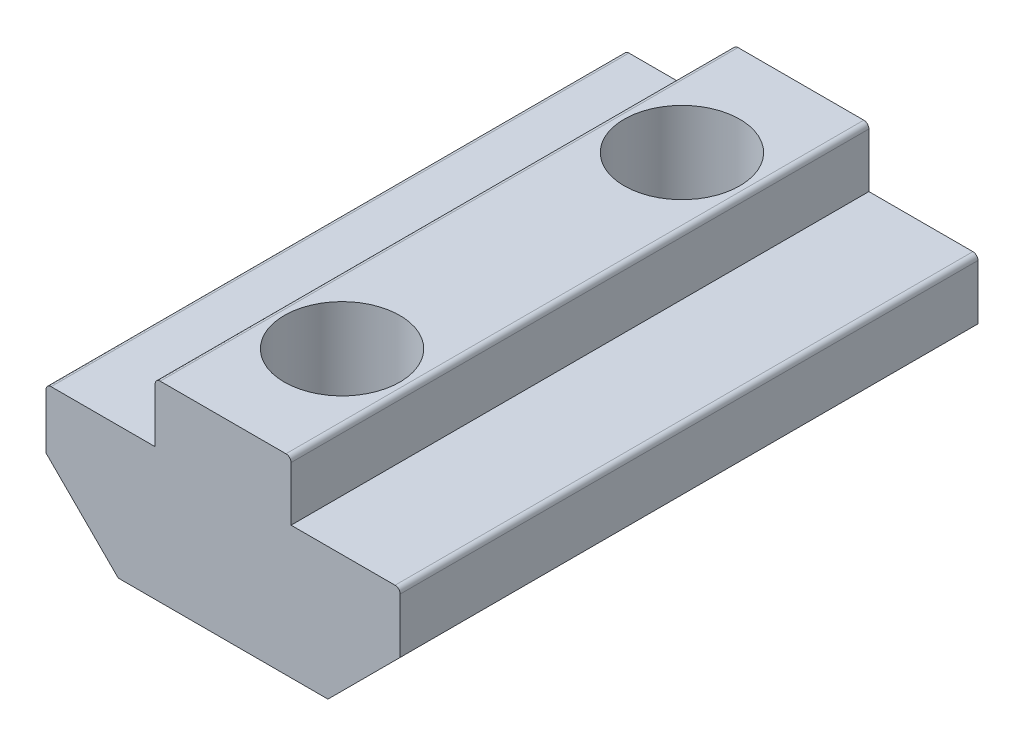
SolidWorks part; units mm, degrees
ref_plane "前视基准面" through (0, 0, 0) normal (0, 0, 1) x (1, 0, 0)
ref_plane "上视基准面" through (0, 0, 0) normal (0, 1, 0) x (1, 0, 0)
ref_plane "右视基准面" through (0, 0, 0) normal (1, 0, 0) x (0, 0, -1)
sketch "草图1" plane through (0, 0, 0) normal (0, 0, 1) x (1, 0, 0)
  line L0 (-6.35, -5.1808) -> (5.99, -5.1808)
  line L1 (-10.3, 2.5992) -> (-4.18, 2.5992)
  line L2 (3.82, 2.5992) -> (9.94, 2.5992)
  line L3 (10.24, -0.9308) -> (10.24, 2.2992)
  line L4 (3.52, 6.0892) -> (-3.88, 6.0892)
  line L5 (-10.6, 2.2992) -> (-10.6, -0.9308)
  line L6 (3.82, 5.7892) -> (3.82, 2.5992)
  line L7 (-4.18, 5.7892) -> (-4.18, 2.5992)
  line L8 (5.99, -5.1808) -> (10.24, -0.9308)
  line L9 (-6.35, -5.1808) -> (-10.6, -0.9308)
  arc A0 (10.24, 2.2992) -> (9.94, 2.5992) centre (9.94, 2.2992) ccw
  arc A1 (-3.88, 6.0892) -> (-4.18, 5.7892) centre (-3.88, 5.7892) ccw
  arc A2 (-10.3, 2.5992) -> (-10.6, 2.2992) centre (-10.3, 2.2992) ccw
  arc A3 (3.82, 5.7892) -> (3.52, 6.0892) centre (3.52, 5.7892) ccw
extrude "凸台-拉伸1" add sketch "草图1" along normal blind 34
hole_wizard "M8 螺纹孔1" positions "草图3" profile "草图2" tap size "M8" standard "GB" end condition through all
sketch "草图3" plane through (0, 6.0892, 0) normal (0, 1, 0) x (-1, 0, 0)
  line L0 (-3.52, 34) -> (3.88, 34) construction
  line L1 (-10.24, 17) -> (11.7474, 17) construction
  line L2 (-10.24, 34) -> (-10.24, 0) construction
  point P0 (0.18, 7)
  point P1 (0.18, 27)
  point P6 (0.18, 34)
  dimension "D1" = 20
sketch "草图2" plane through (-0.18, 6.0892, 7) normal (1, 0, 0) x (0, 0, 1)
  line L0 (0, 0) -> (0, 11.27)
  line L1 (0, 11.27) -> (3.4, 11.27)
  line L2 (3.4, 11.27) -> (3.4, 0)
  line L5 (3.4, 0) -> (0, 0)
  line L11 (0, -6.35) -> (0, 107.95) construction
  dimension "通孔螺纹孔钻头直径" = 6.8
  dimension "通孔螺纹孔钻头深度" = 11.27
cosmetic thread "孔螺蚊线1" parameters "D2"=8
cosmetic thread "孔螺蚊线2" parameters "D2"=8
